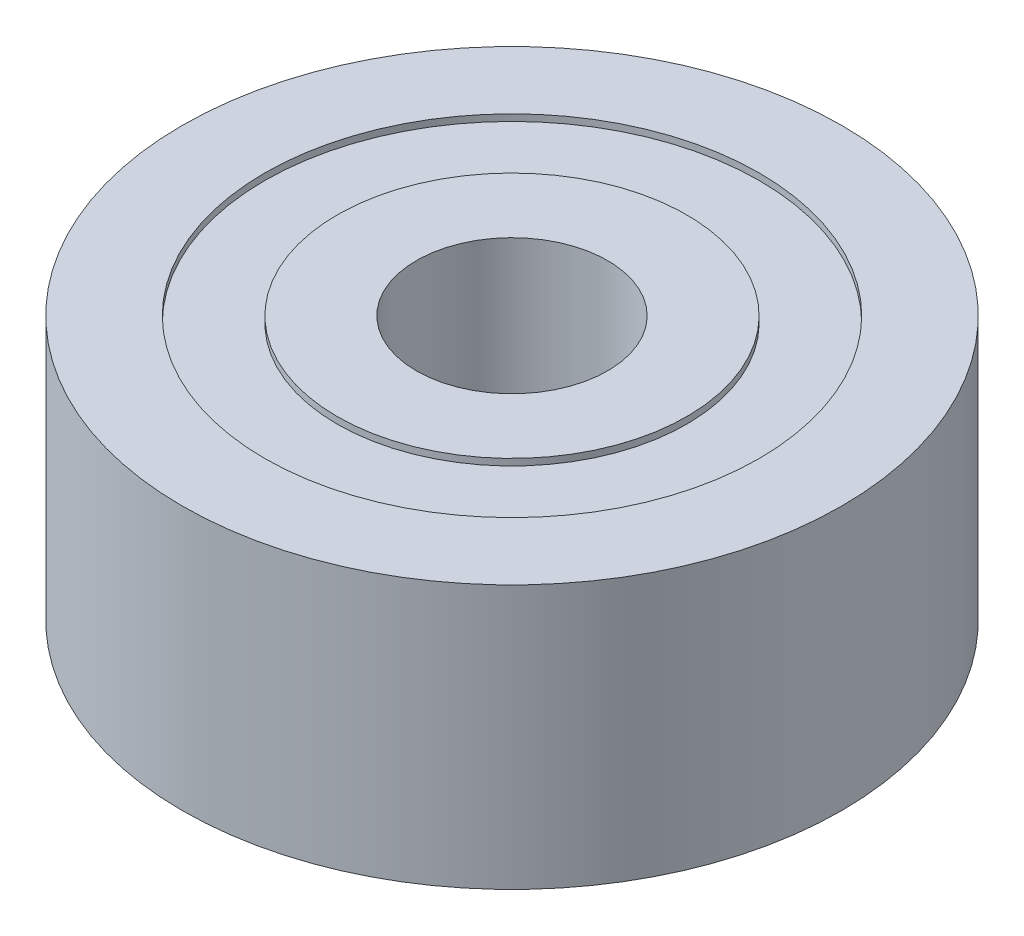
SolidWorks part; units mm, degrees
ref_plane "Спереди" through (0, 0, 0) normal (0, 0, 1) x (1, 0, 0)
ref_plane "Сверху" through (0, 0, 0) normal (0, 1, 0) x (1, 0, 0)
ref_plane "Справа" through (0, 0, 0) normal (1, 0, 0) x (0, 0, -1)
sketch "Эскиз1" plane through (0, 0, 0) normal (0, 1, 0) x (1, 0, 0)
  circle A0 centre (0, 0) radius 1.45
  circle A1 centre (0, 0) radius 5
  dimension "D1" = 2.9
  dimension "D2" = 10
extrude "Бобышка-Вытянуть1" add sketch "Эскиз1" along normal mid plane 4
sketch "Эскиз2" plane through (0, 2, 0) normal (0, 1, 0) x (1, 0, 0)
  circle A0 centre (0, 0) radius 2.65
  circle A1 centre (0, 0) radius 3.75
  dimension "D1" = 5.3
  dimension "D2" = 7.5
extrude "Вырез-Вытянуть1" cut sketch "Эскиз2" against normal blind 0.1
mirror "Зеркальное отражение1" about plane through (0, 0, 0) normal (0, 1, 0) of "Вырез-Вытянуть1"
equation "\"big_bearing_d1\"= 19.9"
equation "\"big_bearing_d2\"= 42"
equation "\"big_bearing_h\"= 11.9"
equation "\"print_offset\"= 0.5"
equation "\"small_bearing_d1\"= 2.9"
equation "\"small_bearing_d2\"= 10"
equation "\"small_bearing_h\"= 4"
equation "\"tube_d\"= 16"
equation "\"small_bearing_distance\"= 2"
equation "\"D1@Эскиз1\"=\"small_bearing_d1\""
equation "\"D2@Эскиз1\"=\"small_bearing_d2\""
equation "\"D1@Бобышка-Вытянуть1\"=\"small_bearing_h\""
